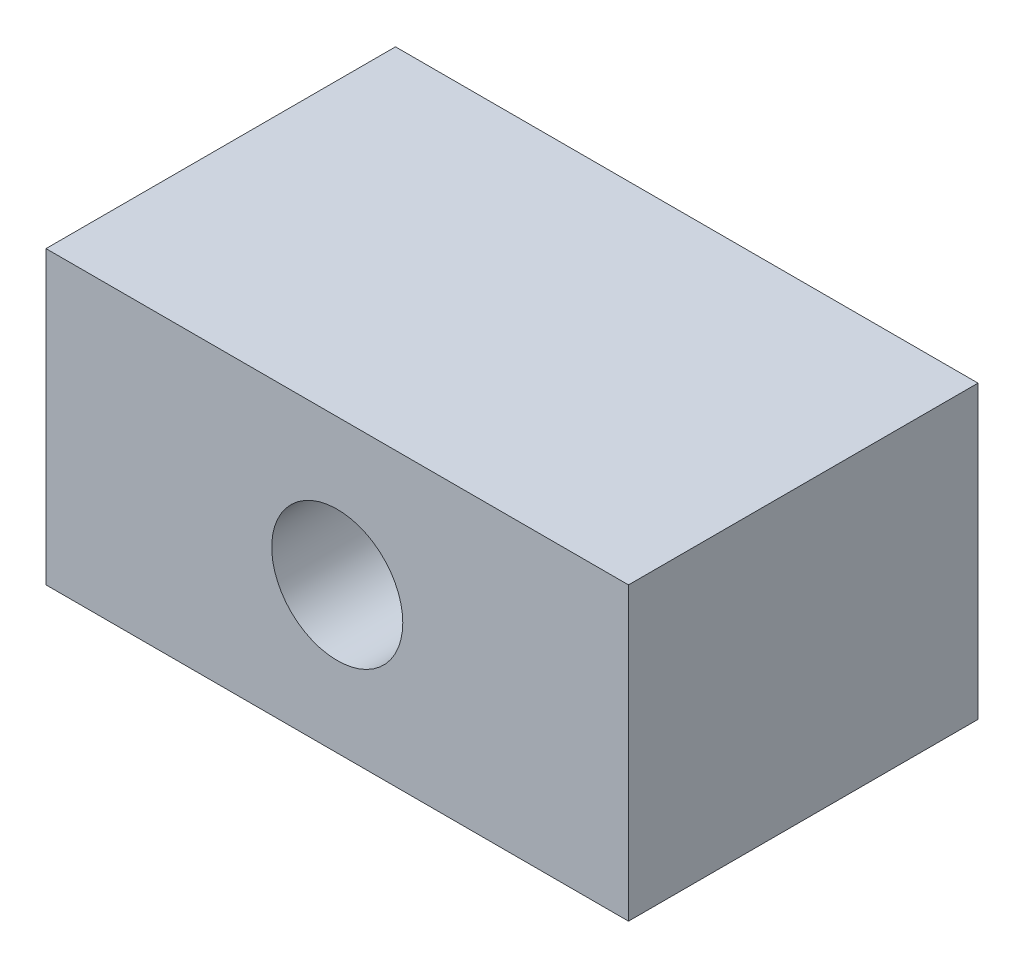
SolidWorks part; units mm, degrees
material "1060 Alloy"
ref_plane "Front Plane" through (0, 0, 0) normal (0, 0, 1) x (1, 0, 0)
ref_plane "Top Plane" through (0, 0, 0) normal (0, 1, 0) x (1, 0, 0)
ref_plane "Right Plane" through (0, 0, 0) normal (1, 0, 0) x (0, 0, -1)
sketch "BaseSketch" plane through (0, 0, 0) normal (0, 1, 0) x (1, 0, 0)
  line L1 (100, -60) -> (-100, -60)
  line L2 (100, -60) -> (100, 60)
  line L3 (100, 60) -> (-100, 60)
  line L4 (-100, -60) -> (-100, 60)
  line L5 (100, -60) -> (-100, 60) construction
  line L6 (100, 60) -> (-100, -60) construction
  point P0 (0, 0)
  dimension "L" = 200
  dimension "W" = 120
extrude "Boss-Extrude1" add sketch "BaseSketch" along normal blind 100
sketch "Sketch2" plane through (0, 0, 60) normal (0, 0, 1) x (1, 0, 0)
  circle A0 centre (0, 50) radius 22.5
  point P2 (0, 0)
  dimension "R" = 45
  dimension "D" = 50
extrude "Cut-Extrude1" cut sketch "Sketch2" against normal through all
